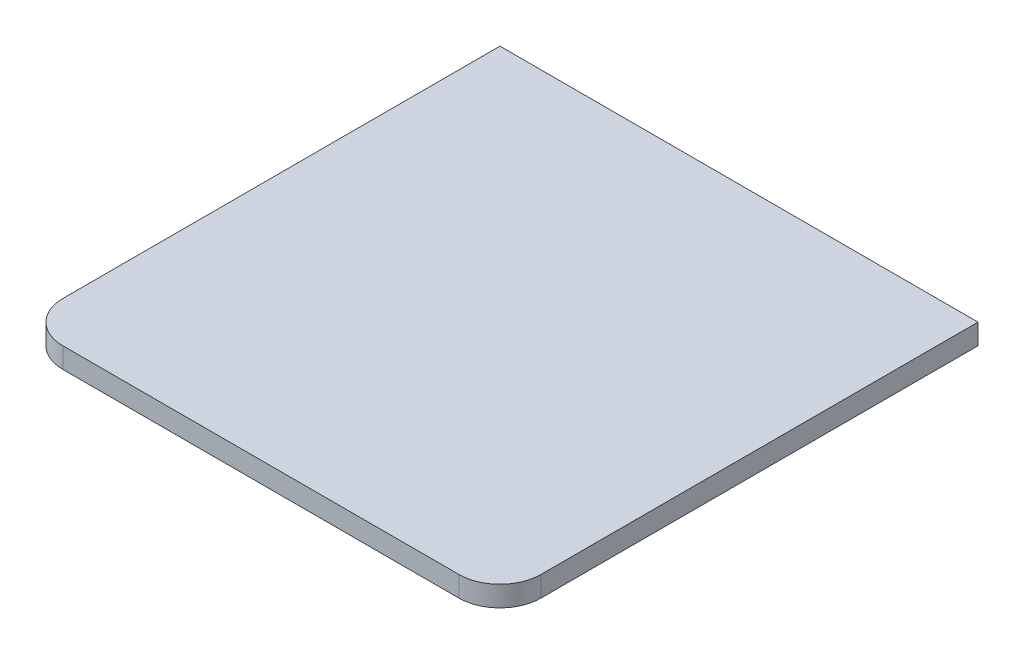
SolidWorks part; units mm, degrees
material "ASTM A36 Steel"
ref_plane "Front Plane" through (0, 0, 0) normal (0, 0, 1) x (1, 0, 0)
ref_plane "Top Plane" through (0, 0, 0) normal (0, 1, 0) x (1, 0, 0)
ref_plane "Right Plane" through (0, 0, 0) normal (1, 0, 0) x (0, 0, -1)
sketch "Sketch1" plane through (0, 0, 0) normal (0, 1, 0) x (1, 0, 0)
  line L1 (-35, 35) -> (35, 35)
  line L2 (-35, 35) -> (-35, -35)
  line L3 (-35, -35) -> (35, -35)
  line L4 (35, 35) -> (35, -35)
  line L5 (-35, 35) -> (35, -35) construction
  line L6 (-35, -35) -> (35, 35) construction
  point P0 (0, 0)
extrude "Boss-Extrude1" add sketch "Sketch1" along normal blind 3
fillet "Fillet1" radius 6 2 edges at (-35, 1.5, 35) (35, 1.5, 35)
